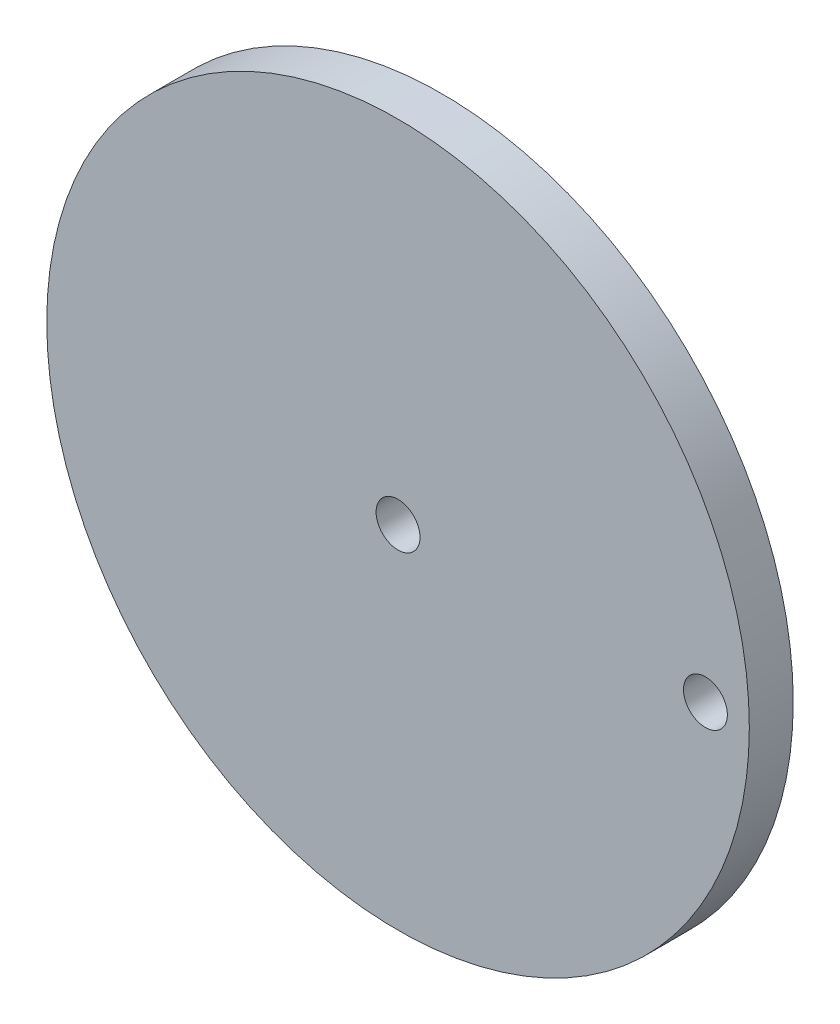
SolidWorks part; units mm, degrees
ref_plane "前视基准面" through (0, 0, 0) normal (0, 0, 1) x (1, 0, 0)
ref_plane "上视基准面" through (0, 0, 0) normal (0, 1, 0) x (1, 0, 0)
ref_plane "右视基准面" through (0, 0, 0) normal (1, 0, 0) x (0, 0, -1)
sketch "草图1" plane through (0, 0, 0) normal (0, 0, 1) x (1, 0, 0)
  line L0 (0, -5) -> (35, -5)
  line L1 (0, 5) -> (35, 5)
  line L3 (49.608, 5) -> (50.9135, 5)
  circle A0 centre (0, 0) radius 5
  circle A1 centre (35, 0) radius 5
  circle A2 centre (35, 0) radius 2.5
  circle A3 centre (0, 0) radius 2.5
  dimension "D1" = 35
  dimension "D2" = 10
  dimension "D3" = 5
  dimension "D4" = 5
extrude "凸台-拉伸1" add sketch "草图1" along normal blind 5 contours A1 L1 A0 L0 | A0 A3 | A1 A2
sketch "草图2" plane through (0, 0, 5) normal (0, 0, 1) x (1, 0, 0)
  circle A0 centre (0, 0) radius 40
  circle A1 centre (0, 0) radius 2.5
  circle A2 centre (35, 0) radius 2.5
extrude "凸台-拉伸2" add sketch "草图2" against normal blind 5
